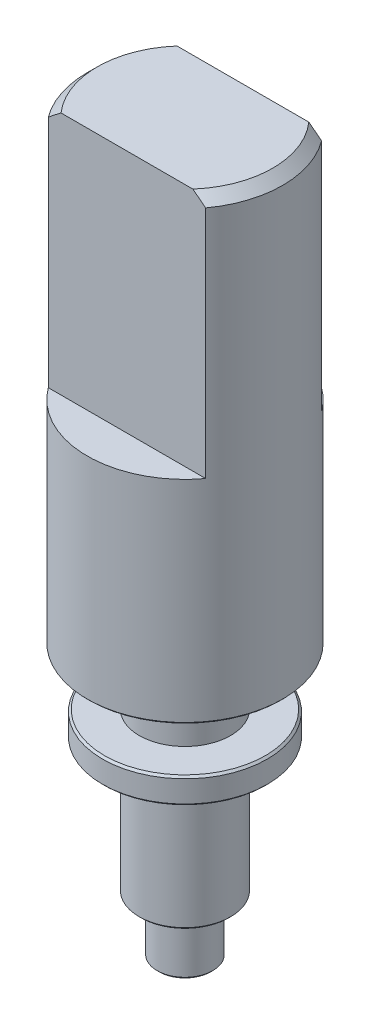
SolidWorks part; units mm, degrees
material "Латунь ЛС59  ГОСТ 15527-70"
ref_plane "Спереди" through (0, 0, 0) normal (0, 0, 1) x (1, 0, 0)
ref_plane "Сверху" through (0, 0, 0) normal (0, 1, 0) x (1, 0, 0)
ref_plane "Справа" through (0, 0, 0) normal (1, 0, 0) x (0, 0, -1)
sketch "Эскиз1" plane through (0, 0, 0) normal (0, 0, 1) x (1, 0, 0)
  line L0 (0, 18.3) -> (0, 0)
  line L1 (0, 0) -> (-0.7, 0)
  line L2 (-0.7, 0) -> (-0.7, 1.4)
  line L3 (-1.15, 4.75) -> (-2.075, 4.75)
  line L4 (-2.075, 4.75) -> (-2.075, 5.4)
  line L5 (-2.075, 5.4) -> (-1.15, 5.4)
  line L6 (-1.15, 5.4) -> (-1.15, 6.8)
  line L7 (-1.15, 6.8) -> (-2.46, 6.8)
  line L8 (-2.46, 6.8) -> (-2.46, 18.3)
  line L9 (-2.46, 18.3) -> (0, 18.3)
  line L10 (-0.7, 1.4) -> (-1.15, 1.4)
  line L11 (-1.15, 1.4) -> (-1.15, 4.75)
  dimension "D1" = 18.3
  dimension "D2" = 0.7
  dimension "D3" = 1.15
  dimension "D4" = 1.4
  dimension "D5" = 3.35
  dimension "D6" = 2.075
  dimension "D7" = 0.65
  dimension "D8" = 6.8
  dimension "D9" = 2.46
revolve "Повернуть1" add sketch "Эскиз1" angle 360 about L0
sketch "Эскиз2" plane through (0, 18.3, 0) normal (0, 1, 0) x (1, 0, 0)
  line L0 (-1.9799, 1.46) -> (1.9799, 1.46)
  line L1 (-1.9799, -1.46) -> (1.9799, -1.46)
  circle A0 centre (0, 0) radius 2.46 construction
  arc A1 (-1.9799, -1.46) -> (1.9799, -1.46) centre (0, 0) ccw
  arc A2 (1.9799, 1.46) -> (-1.9799, 1.46) centre (0, 0) ccw
  dimension "D1" = 1.46
  dimension "D2" = 2.92
extrude "Вырез-Вытянуть1" cut sketch "Эскиз2" against normal blind 6.15
chamfer "Фаска1" distance 0.25 angle 45 2 edges at (-2.46, 18.3, 0) (2.46, 18.3, 0)
chamfer "Фаска2" distance 0.05 angle 45 5 edges at (0, 0, 0.7) (0, 5.4, 2.075) (0, 4.75, 2.075) (0, 6.8, 2.46) (0, 1.4, 1.15)
